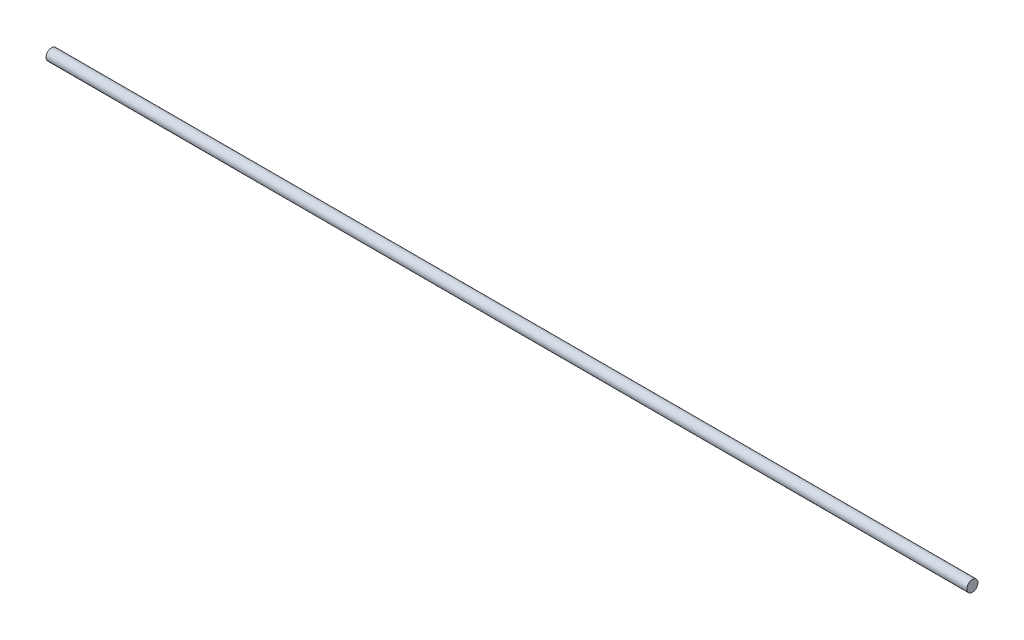
SolidWorks part; units mm, degrees
material "Aço inoxidável fundido"
ref_plane "Plano frontal" through (0, 0, 0) normal (0, 0, 1) x (1, 0, 0)
ref_plane "Plano superior" through (0, 0, 0) normal (0, 1, 0) x (1, 0, 0)
ref_plane "Plano direito" through (0, 0, 0) normal (1, 0, 0) x (0, 0, -1)
sketch "Esboço1" plane through (0, 0, 0) normal (1, 0, 0) x (0, 0, -1)
  circle A0 centre (0, 0) radius 2.5
  dimension "D1" = 5
extrude "Ressalto-extrusão1" add sketch "Esboço1" along normal mid plane 412
